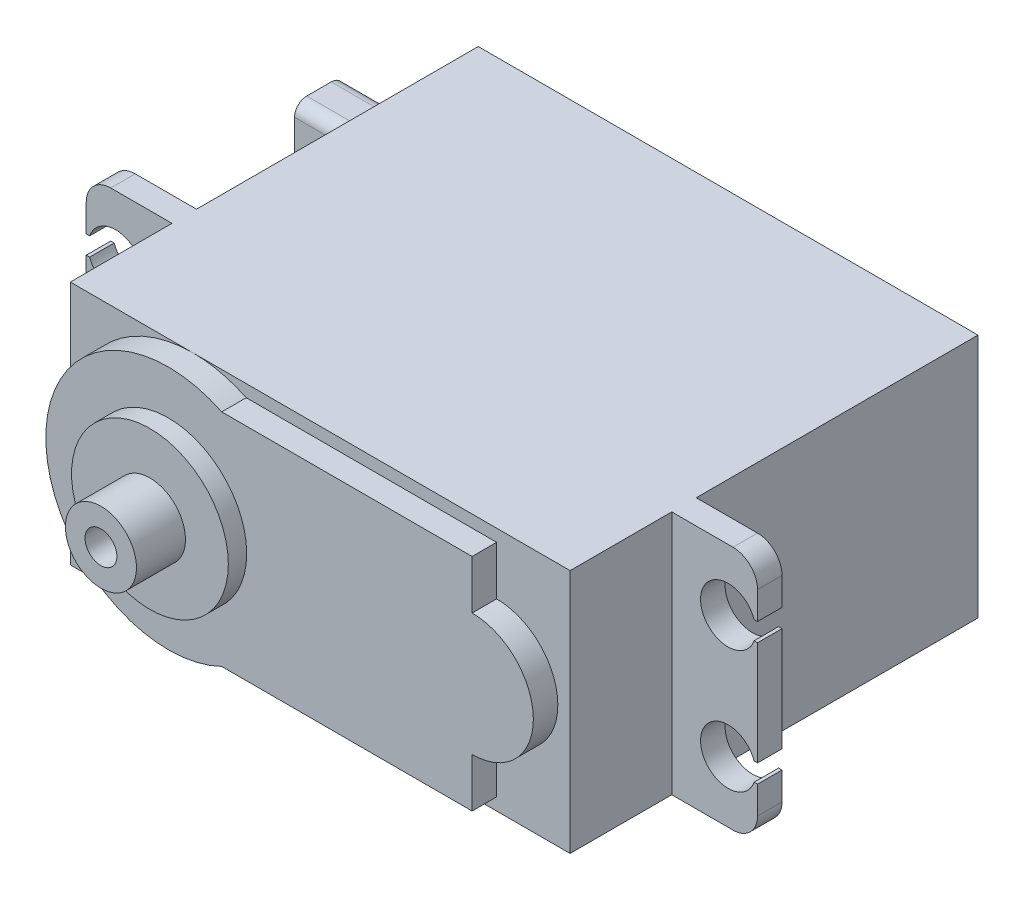
SolidWorks part; units mm, degrees
ref_plane "Plan de face" through (0, 0, 0) normal (0, 0, 1) x (1, 0, 0)
ref_plane "Plan de dessus" through (0, 0, 0) normal (0, 1, 0) x (1, 0, 0)
ref_plane "Plan de droite" through (0, 0, 0) normal (1, 0, 0) x (0, 0, -1)
sketch "Esquisse1" plane through (0, 0, 0) normal (0, 0, 1) x (1, 0, 0)
  line L1 (0, 0) -> (40.8, 0)
  line L2 (0, 0) -> (0, 20)
  line L3 (0, 20) -> (40.8, 20)
  line L4 (40.8, 0) -> (40.8, 20)
  dimension "D1" = 20
  dimension "D2" = 40.8
extrude "Boss.-Extru.1" add sketch "Esquisse1" along normal blind 35.3
sketch "Esquisse2" plane through (0, 0, 35.3) normal (0, 0, 1) x (1, 0, 0)
  line L0 (0, 10) -> (40.8, 10) construction
  line L1 (0, 20) -> (0, 0) construction
  line L2 (40.8, 0) -> (40.8, 20) construction
  line L3 (40.8, 20) -> (0, 20) construction
  line L4 (14.3589, 19) -> (34.8, 19)
  line L5 (34.8, 19) -> (34.8, 15)
  line L6 (34.8, 1) -> (34.8, 5)
  line L7 (14.3589, 1) -> (34.8, 1)
  arc A0 (14.3589, 19) -> (14.3589, 1) centre (10, 10) ccw
  arc A1 (34.8, 5) -> (34.8, 15) centre (34.8, 10) ccw
  dimension "D3" = 10
  dimension "D1" = 1
  dimension "D2" = 6
extrude "Boss.-Extru.2" add sketch "Esquisse2" along normal blind 2
sketch "Esquisse3" plane through (0, 0, 37.3) normal (0, 0, 1) x (1, 0, 0)
  circle A0 centre (10, 10) radius 6.4
  dimension "D1" = 12.8
extrude "Boss.-Extru.3" add sketch "Esquisse3" along normal blind 1.5
sketch "Esquisse4" plane through (0, 0, 38.8) normal (0, 0, 1) x (1, 0, 0)
  circle A0 centre (10, 10) radius 2.9
  circle A1 centre (10, 10) radius 1.3
  dimension "D1" = 5.8
  dimension "D2" = 2.6
extrude "Boss.-Extru.4" add sketch "Esquisse4" along normal blind 4
ref_plane "Plan1" through (0, 0, 27) normal (0, 0, -1) x (-1, 0, 0)
sketch "Esquisse5" plane through (0, 0, 27) normal (0, 0, -1) x (-1, 0, 0)
  line L0 (-20.4, 0) -> (-20.4, 26.1682) construction
  line L1 (-40.8, 20) -> (-47.8, 20)
  line L2 (-40.8, 20) -> (-40.8, 0)
  line L3 (-40.8, 0) -> (-47.8, 0)
  line L4 (-47.8, 20) -> (-47.8, 0)
  line L5 (0, 0) -> (-40.8, 0) construction
  line L6 (0, 0) -> (7, 0)
  line L7 (7, 20) -> (7, 0)
  line L8 (0, 20) -> (0, 0)
  line L9 (0, 20) -> (7, 20)
  dimension "D1" = 7
extrude "Boss.-Extru.5" add sketch "Esquisse5" along normal blind 2
sketch "Esquisse6" plane through (0, 0, 27) normal (0, 0, 1) x (1, 0, 0)
  line L0 (-7, 10) -> (47.8, 10) construction
  line L1 (-7, 0) -> (-7, 20) construction
  line L2 (47.8, 20) -> (47.8, 0) construction
  line L3 (20.4, 10) -> (20.4, 29.0033) construction
  line L4 (-6.7213, 15.75) -> (-7, 15.75)
  line L5 (-7, 15.75) -> (-7, 14.25)
  line L6 (-4.6, 15) -> (-8.4032, 15) construction
  line L7 (-6.7213, 14.25) -> (-7, 14.25)
  line L8 (47.5213, 14.25) -> (47.8, 14.25)
  line L9 (47.8, 15.75) -> (47.8, 14.25)
  line L10 (47.5213, 15.75) -> (47.8, 15.75)
  line L11 (47.5213, 4.25) -> (47.8, 4.25)
  line L12 (47.8, 4.25) -> (47.8, 5.75)
  line L13 (47.5213, 5.75) -> (47.8, 5.75)
  line L14 (-4.6, 5) -> (-8.4032, 5) construction
  line L15 (-6.7213, 5.75) -> (-7, 5.75)
  line L16 (-7, 4.25) -> (-7, 5.75)
  line L17 (-6.7213, 4.25) -> (-7, 4.25)
  arc A0 (-6.7213, 14.25) -> (-6.7213, 15.75) centre (-4.6, 15) ccw
  arc A1 (47.5213, 14.25) -> (47.5213, 15.75) centre (45.4, 15) cw
  arc A2 (47.5213, 5.75) -> (47.5213, 4.25) centre (45.4, 5) ccw
  arc A3 (-6.7213, 5.75) -> (-6.7213, 4.25) centre (-4.6, 5) cw
  point P17 (-7, 15)
  point P31 (-7, 5)
  dimension "D1" = 2.25
  dimension "D2" = 50
  dimension "D3" = 10
  dimension "D4" = 1.5
extrude "Enlèv. mat.-Extru.1" cut sketch "Esquisse6" against normal through all
fillet "Congé1" radius 2 4 edges at (47.8, 20, 26) (47.8, 0, 26) (-7, 20, 26) (-7, 0, 26)
sketch "Esquisse7" plane through (0, 0, 0) normal (-1, 0, 0) x (0, 0, 1)
  line L0 (0, 10) -> (20.5185, 10) construction
  line L1 (0, 20) -> (0, 0) construction
  line L3 (3, 13.5) -> (7, 13.5)
  line L4 (3, 13.5) -> (3, 6.5)
  line L5 (3, 6.5) -> (7, 6.5)
  line L6 (7, 13.5) -> (7, 6.5)
  line L7 (3, 13.5) -> (7, 6.5) construction
  line L8 (3, 6.5) -> (7, 13.5) construction
  point P4 (5, 10)
  dimension "D1" = 7
  dimension "D2" = 4
  dimension "D3" = 3
extrude "Boss.-Extru.6" add sketch "Esquisse7" along normal blind 10
chamfer "Chanfrein1" distance 2 angle 45 4 edges at (20.4, 20, 0) (40.8, 10, 0) (20.4, 0, 0) (0, 10, 0)
fillet "Congé2" radius 1 4 edges at (-5, 13.5, 7) (-5, 13.5, 3) (-5, 6.5, 3) (-5, 6.5, 7)
ref_plane "Plan2" through (0, 10, 0) normal (0, 1, 0) x (1, 0, 0)
